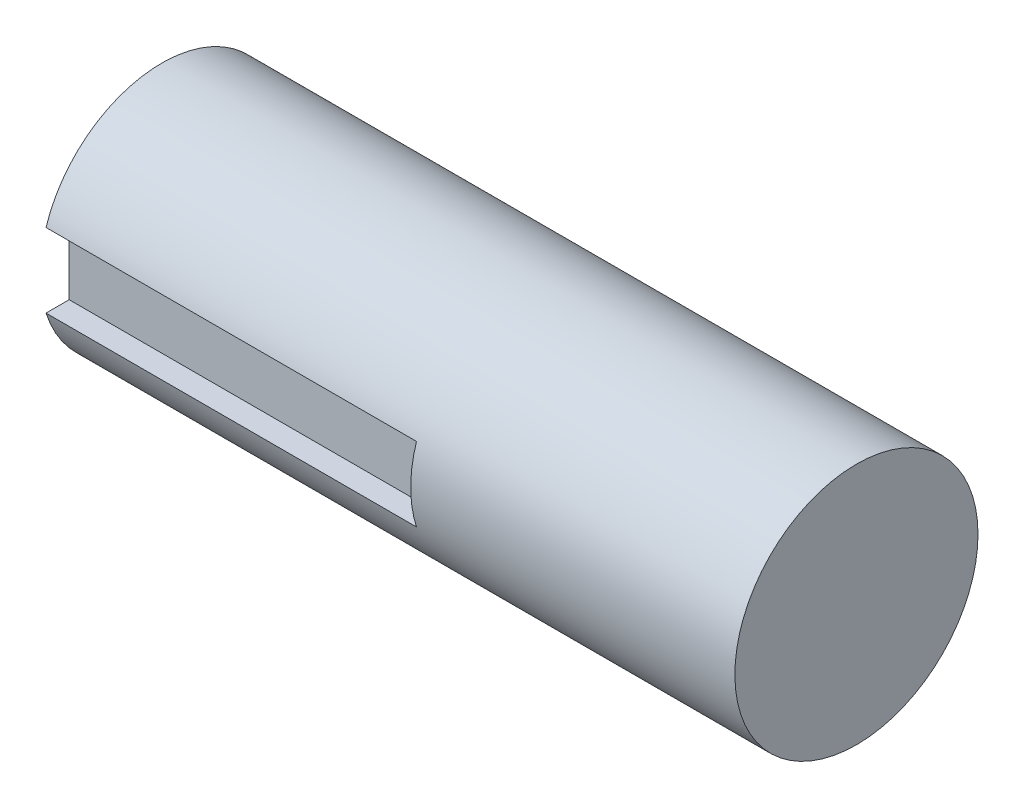
SolidWorks part; units mm, degrees
ref_plane "Front Plane" through (0, 0, 0) normal (1, 0, 0) x (0, 1, 0)
ref_plane "Top Plane" through (0, 0, 0) normal (0, 0, 1) x (0, 1, 0)
ref_plane "Right Plane" through (0, 0, 0) normal (0, 1, 0) x (-1, 0, 0)
sketch "Sketch1" plane through (0, 0, 0) normal (1, 0, 0) x (0, 1, 0)
  circle A0 centre (0, 0) radius 52.5
  dimension "D1" = 105
extrude "Boss-Extrude1" add sketch "Sketch1" along normal blind 300
sketch "Sketch2" plane through (0, 0, 0) normal (-1, 0, 0) x (0, -1, 0)
  line L1 (-16, 40.0025) -> (16, 40.0025)
  line L2 (-16, 40.0025) -> (-16, 50.0025)
  line L4 (16, 40.0025) -> (16, 50.0025)
  line L5 (-16, 40.0025) -> (16, 50.0025) construction
  line L6 (-16, 50.0025) -> (16, 40.0025) construction
  circle A1 centre (0, 0) radius 52.5
  arc A2 (16, 50.0025) -> (-16, 50.0025) centre (0, 0) ccw
  point P0 (0, 45.0025)
  point P8 (0, 0)
  dimension "D2" = 10
  dimension "D3" = 32
  dimension "D1" = 0
extrude "Cut-Extrude1" cut sketch "Sketch2" against normal blind 160
